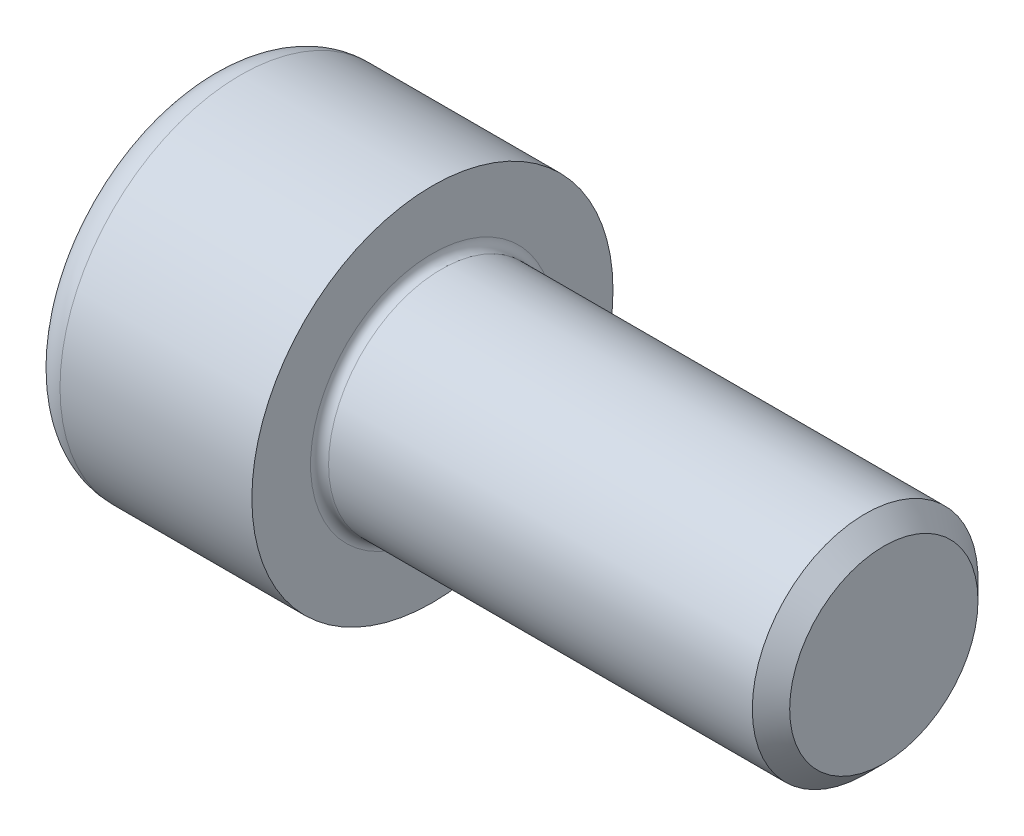
SolidWorks part; units mm, degrees
ref_plane "Plane1" through (0, 0, 0) normal (0, 0, 1) x (1, 0, 0)
ref_plane "Plane2" through (0, 0, 0) normal (0, 1, 0) x (1, 0, 0)
ref_plane "Plane3" through (0, 0, 0) normal (1, 0, 0) x (0, 0, -1)
sketch "BodySke" plane through (0, 0, 0) normal (0, 0, 1) x (1, 0, 0)
  line L0 (0, 0) -> (0, 8)
  line L1 (0, 8) -> (10, 8)
  line L2 (10, 8) -> (10, 5)
  line L3 (10, 5) -> (29.172, 5)
  line L4 (30, 4.172) -> (30, 0)
  line L5 (30, 0) -> (0, 0)
  line L6 (-31.75, 0) -> (127, 0) construction
  line L8 (30, 4.172) -> (29.172, 5)
  line L10 (30, -4.172) -> (29.172, -5) construction
  line L11 (11.5, 9.525) -> (11.5, 3.175) construction
  line L12 (10, 9.525) -> (10, 3.175) construction
  line L13 (-30, 9.525) -> (-30, 3.175) construction
  dimension "Diameter" = 10
  dimension "Head_ht" = 10
  dimension "Length" = 20
  dimension "Body_ch_ang" = 45
  dimension "Head_dia" = 16
  dimension "Minor_dia" = 8.344
  dimension "Advance" = 1.5
  dimension "Thread_nom" = 20
  dimension "Thread_length" = 60
revolve "Base-Revolve" add sketch "BodySke"
cosmetic thread "ThreadCosmetic"
fillet "Fillet1" radius 0.4 1 edges at (10, 0, 5)
fillet "Fillet2" radius 1.5 1 edges at (0, 0, 8)
sketch "Sketch2" plane through (0, 0, 0) normal (0, 0, 1) x (1, 0, 0)
  line L0 (0, 4.0575) -> (5, 4.0575)
  line L1 (5, 4.0575) -> (7.3426, 0)
  line L2 (-31.75, 0) -> (127, 0) construction
  line L3 (7.3426, 0) -> (0, 0)
  line L4 (0, 0) -> (0, 4.0575)
  line L6 (0, 0) -> (47.625, 0) construction
  dimension "D1" = 4.0575
  dimension "D2" = 60
  dimension "Depth" = 5
revolve "Hex-PreBroach" cut sketch "Sketch2" angle 360 about L6
sketch "Sketch3" plane through (0, 0, 0) normal (-1, 0, 0) x (0, 0.5, 0.866)
  line L0 (2.3426, 4.0575) -> (-2.3426, 4.0575)
  line L1 (-2.3426, 4.0575) -> (-4.6852, 0)
  line L2 (2.3426, 4.0575) -> (4.6852, 0)
  line L3 (2.3426, -4.0575) -> (4.6852, 0)
  line L4 (2.3426, -4.0575) -> (-2.3426, -4.0575)
  line L5 (-2.3426, -4.0575) -> (-4.6852, 0)
  dimension "D1" = 4.0575
  dimension "D2" = 4.0575
  dimension "Hex_size" = 8.115
extrude "Hex" cut sketch "Sketch3" against normal blind 5
sketch "ThdSchSke" plane through (0, 0, 0) normal (0, 0, 1) x (1, 0, 0)
  line L0 (14.5, -4.172) -> (13.9202, -5)
  line L1 (14.5, -4.172) -> (15.0798, -5)
  line L2 (15.0798, -5) -> (15.0798, -6.25)
  line L3 (-3.175, 0) -> (5.1513, 0) construction
  line L4 (0, 6.5) -> (0, -6.5) construction
  line L5 (15.0798, -6.25) -> (13.9202, -6.25)
  line L6 (13.9202, -6.25) -> (13.9202, -5)
  dimension "Thread_minor" = 8.344
  dimension "Diameter" = 10
  dimension "Start" = 14.5
  dimension "SideAngle" = 55
  dimension "VeeAngle" = 70
  dimension "Overcut" = 12.5
revolve "ThreadSchematic" [suppressed] cut sketch "ThdSchSke" angle 360 about L3
pattern_linear "ThdSchPat" [suppressed]
equation "\"D2@Sketch3\" = \"Hex_size@Sketch3\" / 2"
equation "\"D1@Sketch3\" = \"Hex_size@Sketch3\" / 2"
equation "\"D1@Sketch2\" = \"Hex_size@Sketch3\" / 2"
equation "\"Thread_minor@ThreadCosmetic\"  =  \"Minor_dia@BodySke\""
equation "\"Depth@Sketch2\" =  \"Key_eng@Hex\""
equation "\"Thread_length@ThreadCosmetic\" = ((sgn( (\"Length@BodySke\" - \"Advance@BodySke\" * 3.0) - \"Thread_nom@BodySke\" )-1)*( (\"Length@BodySke\" - \"Advance@BodySke\" * 3.0) - \"Thread_nom@BodySke\" ))/-2+ \"Thread_nom@BodySke\""
equation "\"Thread_minor@ThdSchSke\" = \"Minor_dia@BodySke\""
equation "\"Diameter@ThdSchSke\" = \"Diameter@BodySke\""
equation "\"Overcut@ThdSchSke\" = \"Diameter@BodySke\" * 1.25"
equation "\"Start@ThdSchSke\" = \"Head_ht@BodySke\" + \"Length@BodySke\" - \"Thread_length@ThreadCosmetic\"  '---Non-countersunk---"
equation "\"Num_threads@ThdSchPat\" = int( \"Thread_length@ThreadCosmetic\" / \"Advance@BodySke\" + 0.999 )  + 1"
equation "\"Advance@ThdSchPat\" = \"Thread_length@ThreadCosmetic\" /  (\"Num_threads@ThdSchPat\" - 1) 'relax it"
equation "\"Num_threads@ThdSchPat\" = \"Num_threads@ThdSchPat\" - sgn( \"Num_threads@ThdSchPat\" - 1) '---chamfered tips only---"
